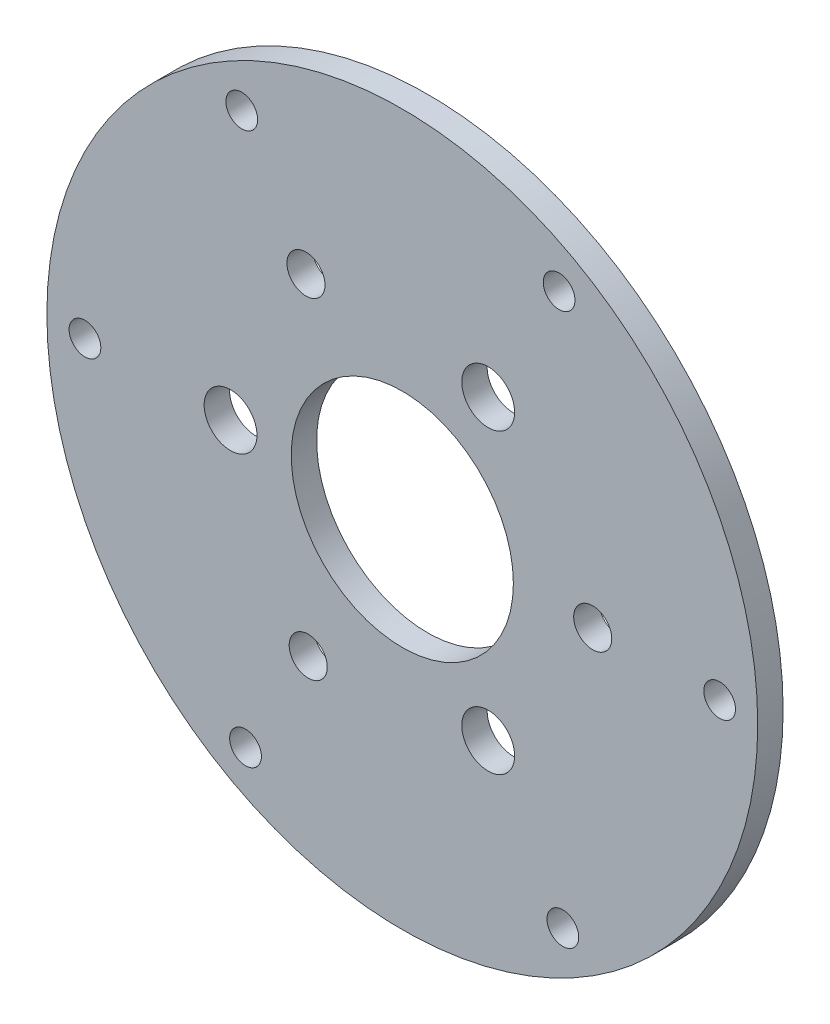
SolidWorks part; units mm, degrees
ref_plane "前视基准面" through (0, 0, 0) normal (0, 0, 1) x (1, 0, 0)
ref_plane "上视基准面" through (0, 0, 0) normal (0, 1, 0) x (1, 0, 0)
ref_plane "右视基准面" through (0, 0, 0) normal (1, 0, 0) x (0, 0, -1)
sketch "草图1" plane through (0, 0, 0) normal (0, 0, 1) x (1, 0, 0)
  line L0 (0, 0) -> (0, -3.3498) construction
  line L1 (0, 0) -> (14.2454, 25.0675) construction
  line L2 (14.2454, 25.0675) -> (12.3519, 21.7355) construction
  line L3 (-13.53, 0) -> (6.765, -11.7173) construction
  line L4 (0, 0) -> (-12.3519, -21.7355) construction
  circle A0 centre (0, 0) radius 15 construction
  circle A1 centre (0, 0) radius 13.53 construction
  circle A8 centre (-13.53, 0) radius 2.08
  circle A9 centre (6.765, 11.7173) radius 2.08
  circle A10 centre (6.765, -11.7173) radius 2.08
  circle A11 centre (0, 0) radius 8.75
  circle A14 centre (0, 0) radius 25 construction
  circle A23 centre (0, 0) radius 28
  circle A30 centre (12.3519, 21.7355) radius 1.25
  circle A31 centre (24.9994, 0.1707) radius 1.25
  circle A32 centre (12.6476, -21.5648) radius 1.25
  circle A33 centre (-12.3519, -21.7355) radius 1.25
  circle A34 centre (-24.9994, -0.1707) radius 1.25
  circle A35 centre (-12.6476, 21.5648) radius 1.25
  circle A36 centre (-7.4111, -13.0413) radius 1.5
  circle A37 centre (-7.5885, 12.9389) radius 1.5
  circle A38 centre (14.9997, 0.1024) radius 1.5
  point P51 (-13, 22.5167)
  point P52 (-13, -22.5167)
  point P53 (26, 0)
  point P54 (-13, 22.5167)
  dimension "D1" = 6
  dimension "D2" = 3
extrude "凸台-拉伸1" add sketch "草图1" along normal blind 2
sketch "草图2" plane through (0, 0, 2) normal (0, 0, 1) x (1, 0, 0)
  circle A0 centre (-24.9994, -0.1707) radius 1.5
  circle A1 centre (-12.6476, 21.5648) radius 1.5
  circle A2 centre (12.3519, 21.7355) radius 1.5
  circle A3 centre (24.9994, 0.1707) radius 1.5
  circle A4 centre (12.6476, -21.5648) radius 1.5
  circle A5 centre (-12.3519, -21.7355) radius 1.5
  dimension "D1" = 6
